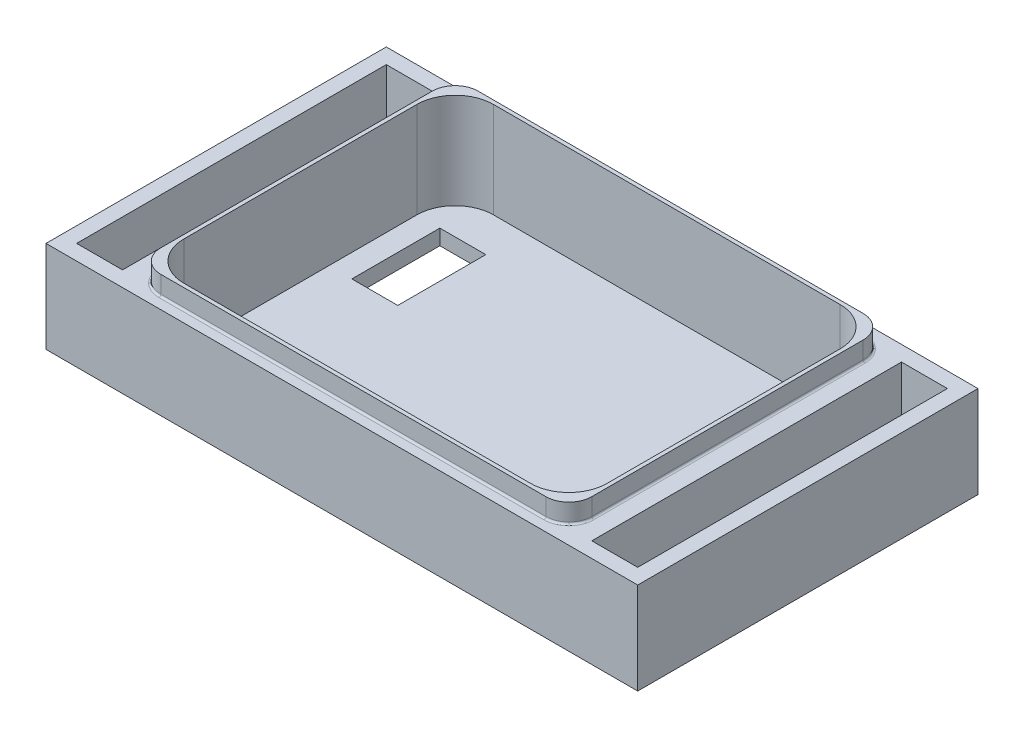
SolidWorks part; units mm, degrees
ref_plane "Front Plane" through (0, 0, 0) normal (0, 0, 1) x (1, 0, 0)
ref_plane "Top Plane" through (0, 0, 0) normal (0, 1, 0) x (1, 0, 0)
ref_plane "Right Plane" through (0, 0, 0) normal (1, 0, 0) x (0, 0, -1)
sketch "Sketch1" plane through (0, 0, 0) normal (0, 1, 0) x (1, 0, 0)
  line L1 (-29.655, 22.23) -> (29.655, 22.23)
  line L2 (-29.655, 22.23) -> (-29.655, -22.23)
  line L3 (-29.655, -22.23) -> (29.655, -22.23)
  line L4 (29.655, 22.23) -> (29.655, -22.23)
  dimension "D1" = 44.46
  dimension "D2" = 22.23
  dimension "D3" = 59.31
  dimension "D4" = 29.655
extrude "Boss-Extrude1" add sketch "Sketch1" along normal blind 2
sketch "Sketch2" plane through (0, 2, 0) normal (0, 1, 0) x (1, 0, 0)
  line L0 (27.655, -20.23) -> (27.655, 20.23)
  line L1 (27.655, 20.23) -> (-27.655, 20.23)
  line L2 (-27.655, 20.23) -> (-27.655, -20.23)
  line L3 (-27.655, -20.23) -> (27.655, -20.23)
  line L4 (-29.655, 22.23) -> (-29.655, -22.23)
  line L5 (-29.655, -22.23) -> (29.655, -22.23)
  line L6 (29.655, -22.23) -> (29.655, 22.23)
  line L7 (29.655, 22.23) -> (-29.655, 22.23)
  line L8 (-29.655, 22.23) -> (-29.655, -22.23)
  line L9 (-29.655, -22.23) -> (29.655, -22.23)
  line L10 (29.655, -22.23) -> (29.655, 22.23)
  line L11 (29.655, 22.23) -> (-29.655, 22.23)
  dimension "D1" = 0
  dimension "D2" = 2
extrude "Boss-Extrude2" add sketch "Sketch2" along normal blind 12.5
sketch "Sketch3" plane through (29.655, 0, 0) normal (1, 0, 0) x (0, 0, -1)
  line L1 (-20.73, 12) -> (-22.23, 12)
  line L2 (-20.73, 12) -> (-20.73, 14.5)
  line L3 (-20.73, 14.5) -> (-22.23, 14.5)
  line L4 (-22.23, 12) -> (-22.23, 14.5)
  dimension "D1" = 1.5
  dimension "D2" = 2.5
sketch "Sketch4" plane through (0, 14.5, 0) normal (0, 1, 0) x (1, 0, 0)
  line L0 (-29.655, -22.23) -> (29.655, -22.23) construction
  line L1 (-29.655, 22.23) -> (-29.655, -22.23) construction
  line L2 (29.655, 22.23) -> (-29.655, 22.23) construction
  line L3 (29.655, -22.23) -> (29.655, 22.23) construction
  line L4 (-29.655, -22.23) -> (29.655, -22.23)
  line L5 (-29.655, 22.23) -> (-29.655, -22.23)
  line L6 (29.655, 22.23) -> (-29.655, 22.23)
  line L7 (29.655, -22.23) -> (29.655, 22.23)
sweep "Cut-Sweep1" cut profiles "Sketch3" path "Sketch4"
sketch "Sketch5" plane through (0, 0, 0) normal (0, -1, 0) x (-1, 0, 0)
  line L0 (29.655, -22.23) -> (29.655, 22.23) construction
  line L1 (24.655, 3.73) -> (18.655, 3.73)
  line L2 (24.655, 3.73) -> (24.655, 15.23)
  line L3 (24.655, 15.23) -> (18.655, 15.23)
  line L4 (18.655, 3.73) -> (18.655, 15.23)
  line L5 (-27.655, 20.23) -> (27.655, 20.23) construction
  dimension "D1" = 11.5
  dimension "D2" = 6
  dimension "D3" = 5
  dimension "D4" = 5
extrude "Cut-Extrude1" cut sketch "Sketch5" against normal blind 10
sketch "Sketch6" plane through (0, 0, 0) normal (0, -1, 0) x (1, 0, 0)
  text T0 "A" font "Century Schoolbook" height in points 72
  dimension "D1" = 8
  dimension "D2" = 8
extrude "Boss-Extrude3" add sketch "Sketch6" along normal blind 2
fillet "Fillet1" radius 5 4 edges at (-27.655, 8.25, -20.23) (27.655, 8.25, -20.23) (27.655, 8.25, 20.23) (-27.655, 8.25, 20.23)
sketch "Sketch7" plane through (0, 0, 0) normal (0, -1, 0) x (1, 0, 0)
  line L0 (-29.655, -22.23) -> (29.655, -22.23) construction
  line L1 (-28.655, -22.23) -> (28.655, -22.23) construction
  line L2 (-28.655, -22.23) -> (-28.655, 22.23) construction
  line L3 (-28.655, 22.23) -> (28.655, 22.23) construction
  line L4 (28.655, -22.23) -> (28.655, 22.23) construction
  line L5 (-29.655, 22.23) -> (29.655, 22.23) construction
  line L6 (-36.655, -20.23) -> (-36.655, 20.23)
  line L7 (-30.655, -22.23) -> (30.655, -22.23) construction
  line L8 (-30.655, -22.23) -> (-30.655, 22.23) construction
  line L9 (-30.655, 22.23) -> (30.655, 22.23) construction
  line L10 (30.655, -22.23) -> (30.655, 22.23) construction
  line L11 (-28.655, -22.23) -> (-38.655, -22.23)
  line L12 (-28.655, -22.23) -> (-28.655, 22.23)
  line L13 (-28.655, 22.23) -> (-38.655, 22.23)
  line L14 (-38.655, -22.23) -> (-38.655, 22.23)
  line L15 (28.655, -22.23) -> (38.655, -22.23)
  line L16 (28.655, -22.23) -> (28.655, 22.23)
  line L17 (28.655, 22.23) -> (38.655, 22.23)
  line L18 (38.655, -22.23) -> (38.655, 22.23)
  line L19 (-30.655, 20.23) -> (-36.655, 20.23)
  line L20 (-30.655, -20.23) -> (-30.655, 20.23)
  line L21 (-30.655, -20.23) -> (-36.655, -20.23)
  line L22 (30.655, 20.23) -> (36.655, 20.23)
  line L23 (36.655, -20.23) -> (36.655, 20.23)
  line L24 (30.655, -20.23) -> (36.655, -20.23)
  line L25 (30.655, -20.23) -> (30.655, 20.23)
  dimension "D1" = 57.31
  dimension "D2" = 44.46
  dimension "D3" = 28.655
  dimension "D4" = 44.46
  dimension "D5" = 61.31
  dimension "D6" = 2
  dimension "D7" = 10
  dimension "D8" = 10
  dimension "D9" = 2
extrude "Boss-Extrude4" add sketch "Sketch7" against normal up to surface (12 mm away) up to face at (28.7175, 12, -10.9275)
fillet "Fillet2" radius 3 4 edges at (-28.155, 13.25, -20.73) (28.155, 13.25, -20.73) (-28.155, 13.25, 20.73)
fillet "Fillet3" radius 0.25 12 edges at (-28.155, 12, 0) (0, 12, -20.73) (-27.9266, 12, -18.8781) (-26.3031, 12, -20.5016) (26.3031, 12, -20.5016) (27.9266, 12, -18.8781) (27.9266, 12, 18.8781) (26.3031, 12, 20.5016) (-26.3031, 12, 20.5016) (-27.9266, 12, 18.8781)
